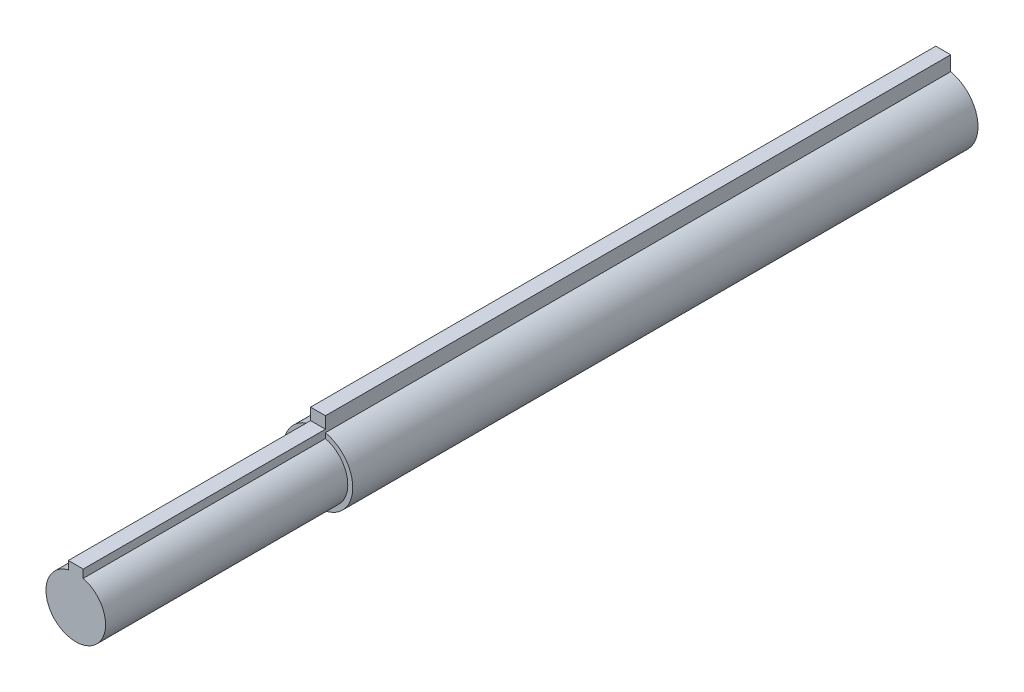
SolidWorks part; units mm, degrees
ref_plane "Front Plane" through (0, 0, 0) normal (0, 0, 1) x (1, 0, 0)
ref_plane "Top Plane" through (0, 0, 0) normal (0, 1, 0) x (1, 0, 0)
ref_plane "Right Plane" through (0, 0, 0) normal (1, 0, 0) x (0, 0, -1)
sketch "Sketch1" plane through (0, 0, 0) normal (0, 0, 1) x (1, 0, 0)
  line L1 (-2.38, 11.818) -> (2.38, 11.818)
  line L2 (-2.38, 11.818) -> (-2.38, 9.228)
  line L4 (2.38, 11.818) -> (2.38, 9.228)
  arc A0 (-2.38, 9.228) -> (2.38, 9.228) centre (0, 0) ccw
  point P3 (0, 9.53)
  point P4 (0, 11.818)
  dimension "D1" = 9.53
  dimension "D2" = 4.76
  dimension "D3" = 2.59
extrude "Boss-Extrude1" add sketch "Sketch1" along normal blind 77.48 contours L1 L4 A0 L2
sketch "Sketch2" plane through (0, 0, 0) normal (0, 0, -1) x (-1, 0, 0)
  line L1 (-2.38, 15.5572) -> (2.38, 15.5572)
  line L2 (-2.38, 15.5572) -> (-2.38, 10.8572)
  line L4 (2.38, 15.5572) -> (2.38, 10.8572)
  arc A0 (-2.38, 10.8572) -> (2.38, 10.8572) centre (0, 0) ccw
  point P3 (0, 11.115)
  point P4 (0, 0)
  point P6 (0, 15.5572)
  dimension "D1" = 22.23
  dimension "D2" = 4.76
  dimension "D3" = 4.7
extrude "Boss-Extrude2" add sketch "Sketch2" along normal blind 200
